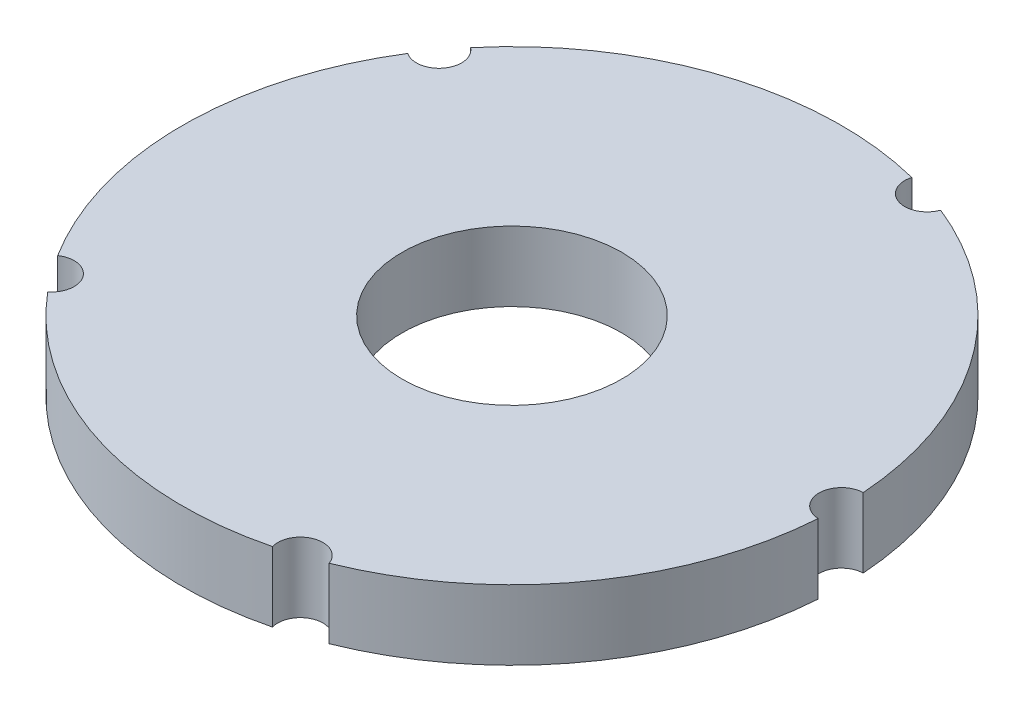
SolidWorks part; units mm, degrees
ref_plane "Front Plane" through (0, 0, 0) normal (0, 0, 1) x (1, 0, 0)
ref_plane "Top Plane" through (0, 0, 0) normal (0, 1, 0) x (1, 0, 0)
ref_plane "Right Plane" through (0, 0, 0) normal (1, 0, 0) x (0, 0, -1)
sketch "Sketch1" plane through (0, 0, 0) normal (0, 1, 0) x (1, 0, 0)
  arc A0 (29.93, 2.0488) -> (11.1974, 27.832) centre (0, 0) ccw
  circle A1 centre (0, 0) radius 10
  arc A2 (29.93, 2.0488) -> (29.93, -2.0488) centre (30, 0) ccw
  arc A3 (11.1974, -27.832) -> (7.3003, -29.0982) centre (9.2705, -28.5317) ccw
  arc A4 (-23.0096, -19.2499) -> (-25.4181, -15.9349) centre (-24.2705, -17.6336) ccw
  arc A5 (-25.4181, 15.9349) -> (-23.0096, 19.2499) centre (-24.2705, 17.6336) ccw
  arc A6 (7.3003, 29.0982) -> (11.1974, 27.832) centre (9.2705, 28.5317) ccw
  arc A7 (-25.4181, 15.9349) -> (-25.4181, -15.9349) centre (0, 0) ccw
  arc A8 (7.3003, 29.0982) -> (-23.0096, 19.2499) centre (0, 0) ccw
  arc A9 (-23.0096, -19.2499) -> (7.3003, -29.0982) centre (0, 0) ccw
  arc A10 (11.1974, -27.832) -> (29.93, -2.0488) centre (0, 0) ccw
  point P17 (0, 0)
  dimension "D1" = 5
extrude "Boss-Extrude1" add sketch "Sketch1" along normal blind 6.35
